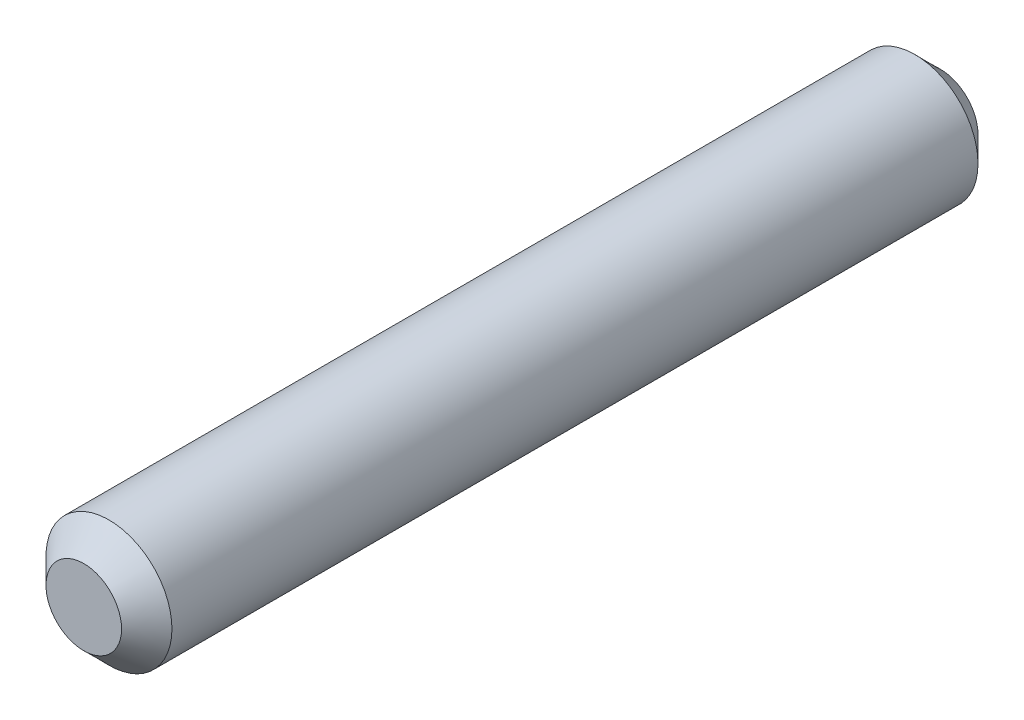
SolidWorks part; units mm, degrees
ref_plane "Front Plane" through (0, 0, 0) normal (0, 0, 1) x (1, 0, 0)
ref_plane "Top Plane" through (0, 0, 0) normal (0, 1, 0) x (1, 0, 0)
ref_plane "Right Plane" through (0, 0, 0) normal (1, 0, 0) x (0, 0, -1)
sketch "Sketch1" plane through (0, 0, 0) normal (0, 0, 1) x (1, 0, 0)
  circle A0 centre (0, 0) radius 1.5875
  dimension "D1" = 3.175
extrude "Boss-Extrude1" add sketch "Sketch1" along normal blind 21.59
chamfer "Chamfer1" distance 0.635 angle 45 2 edges at (1.5875, 0, 0) (1.5875, 0, 21.59)
